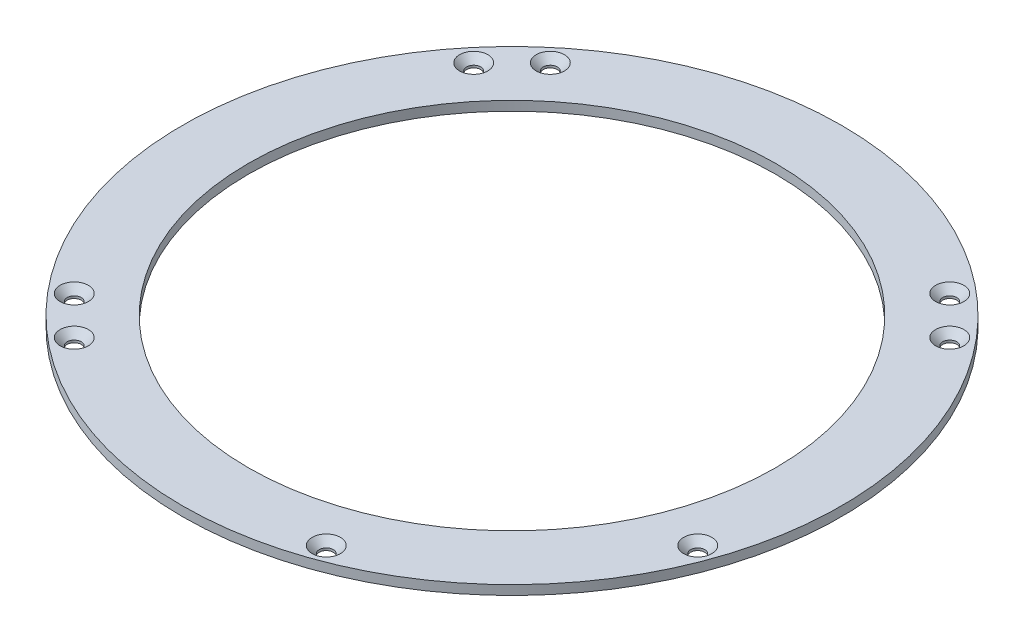
SolidWorks part; units mm, degrees
material "Thornel Mat VMA"
ref_plane "前视基准面" through (0, 0, 0) normal (0, 0, 1) x (1, 0, 0)
ref_plane "上视基准面" through (0, 0, 0) normal (0, 1, 0) x (1, 0, 0)
ref_plane "右视基准面" through (0, 0, 0) normal (1, 0, 0) x (0, 0, -1)
sketch "草图1" plane through (0, 0, 0) normal (0, 1, 0) x (1, 0, 0)
  circle A0 centre (0, 0) radius 70
  circle A1 centre (0, 0) radius 56
  dimension "D1" = 140
  dimension "D2" = 112
extrude "凸台-拉伸1" add sketch "草图1" along normal blind 2
sketch "草图2" plane through (0, 2, 0) normal (0, 1, 0) x (1, 0, 0)
  line L0 (0, 0) -> (0, 70) construction
  line L1 (0, 0) -> (46.669, 46.669) construction
  line L2 (0, 0) -> (42.424, 50.5589) construction
  line L3 (-70, 0) -> (70, 0) construction
  line L4 (0, 0) -> (0, -70) construction
  line L5 (0, 0) -> (46.669, -46.669) construction
  line L6 (0, 0) -> (22.5733, -62.0197) construction
  circle A0 centre (0, 0) radius 66 construction
  circle A1 centre (0, 0) radius 70 construction
  circle A2 centre (42.424, 50.5589) radius 1.5
  circle A3 centre (50.5589, 42.424) radius 1.5
  circle A4 centre (-50.5589, 42.424) radius 1.5
  circle A5 centre (-42.424, 50.5589) radius 1.5
  circle A6 centre (-50.5589, -42.424) radius 1.5
  circle A7 centre (-42.424, -50.5589) radius 1.5
  circle A8 centre (22.5733, -62.0197) radius 1.5
  circle A9 centre (62.0197, -22.5733) radius 1.5
  dimension "D1" = 132
  dimension "D4" = 3
  dimension "D7" = 3
  dimension "D2" = 45
  dimension "D3" = 40
  dimension "D5" = 45
  dimension "D6" = 20
extrude "切除-拉伸1" cut sketch "草图2" against normal blind 3
chamfer "倒角1" distance 1.5 angle 45 8 edges at (62.0197, 2, 21.0733) (50.5589, 2, -43.924) (42.424, 2, -49.0589) (-42.424, 2, -52.0589) (-50.5589, 2, -40.924) (-50.5589, 2, 40.924) (-42.424, 2, 52.0589) (22.5733, 2, 63.5197)
